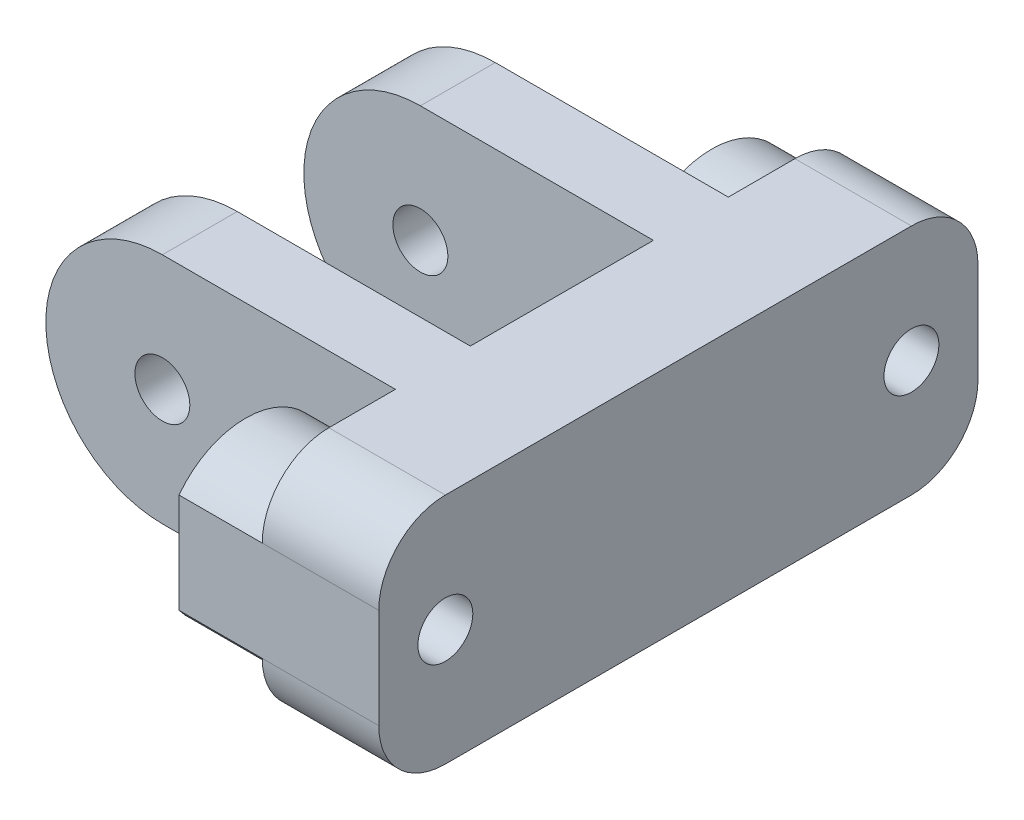
SolidWorks part; units mm, degrees
ref_plane "Front Plane" through (0, 0, 0) normal (0, 0, 1) x (1, 0, 0)
ref_plane "Top Plane" through (0, 0, 0) normal (0, 1, 0) x (1, 0, 0)
ref_plane "Right Plane" through (0, 0, 0) normal (1, 0, 0) x (0, 0, -1)
sketch "Sketch1" plane through (0, 0, 0) normal (0, 0, 1) x (1, 0, 0)
  line L0 (0, 7) -> (14, 7)
  line L1 (14, 7) -> (14, -7)
  line L2 (14, -7) -> (0, -7)
  line L3 (7, 0) -> (14, 0) construction
  circle A0 centre (0, 0) radius 7 construction
  arc A1 (0, 7) -> (0, -7) centre (0, 0) ccw
  circle A2 centre (0, 0) radius 1.65
  dimension "D1" = 14
  dimension "D3" = 3.3
  dimension "D2" = 7
extrude "Boss-Extrude1" add sketch "Sketch1" along normal mid plane 20
sketch "Sketch2" plane through (0, 0, 0) normal (0, 1, 0) x (1, 0, 0)
  line L0 (-7, 10) -> (-7, -10) construction
  line L1 (-7, -5.5) -> (14, -5.5)
  line L2 (-7, -5.5) -> (-7, 5.5)
  line L3 (-7, 5.5) -> (14, 5.5)
  line L4 (14, -5.5) -> (14, 5.5)
  line L5 (14, -10) -> (14, 10) construction
  line L6 (3.5, 10) -> (3.5, 5.5) construction
  line L7 (14, 10) -> (0, 10) construction
  line L8 (3.5, -5.5) -> (3.5, -10) construction
  line L9 (14, -10) -> (0, -10) construction
  dimension "D1" = 11
extrude "Cut-Extrude1" cut sketch "Sketch2" against normal through all both and the other way through all
sketch "Sketch4" plane through (14, 0, 0) normal (1, 0, 0) x (0, 0, -1)
  line L0 (5.5, 7) -> (10, 7) construction
  line L1 (-18, -7) -> (18, -7)
  line L2 (-18, -7) -> (-18, 7)
  line L3 (-18, 7) -> (18, 7)
  line L4 (18, -7) -> (18, 7)
  line L5 (-18, -7) -> (18, 7) construction
  line L6 (-18, 7) -> (18, -7) construction
  line L7 (10, -7) -> (10, 7) construction
  line L8 (10, 7) -> (18, -7) construction
  line L9 (-18, 7) -> (-10, -7) construction
  circle A0 centre (14, 0) radius 1.65
  circle A1 centre (-14, 0) radius 1.65
  point P0 (0, 0)
  dimension "D2" = 3.3
  dimension "D1" = 8
extrude "Boss-Extrude2" add sketch "Sketch4" along normal blind 7
sketch "Sketch5" plane through (14, 0, 0) normal (-1, 0, 0) x (0, 0, 1)
  line L0 (18, 7) -> (18, -7) construction
  line L1 (12.3401, -2.875) -> (15.6599, -2.875)
  line L2 (15.6599, -2.875) -> (17.3198, 0)
  line L3 (17.3198, 0) -> (15.6599, 2.875)
  line L4 (15.6599, 2.875) -> (12.3401, 2.875)
  line L5 (12.3401, 2.875) -> (10.6802, 0)
  line L6 (10.6802, 0) -> (12.3401, -2.875)
  line L7 (10, 7) -> (18, 7) construction
  line L8 (0, 7) -> (0, -7) construction
  line L9 (-5.5, 7) -> (5.5, 7) construction
  line L10 (5.5, -7) -> (-5.5, -7) construction
  line L11 (10, 3) -> (10, -3)
  line L12 (18, 3) -> (18, -3)
  line L13 (10, -7) -> (10, 7) construction
  line L14 (-10.6802, 0) -> (-12.3401, -2.875)
  line L15 (-12.3401, 2.875) -> (-10.6802, 0)
  line L16 (-15.6599, 2.875) -> (-12.3401, 2.875)
  line L17 (-17.3198, 0) -> (-15.6599, 2.875)
  line L18 (-15.6599, -2.875) -> (-17.3198, 0)
  line L19 (-12.3401, -2.875) -> (-15.6599, -2.875)
  line L20 (-18, 3) -> (-18, -3)
  line L21 (-10, 3) -> (-10, -3)
  circle A0 centre (14, 0) radius 2.875 construction
  circle A1 centre (14, 0) radius 4 construction
  arc A2 (10, -3) -> (18, -3) centre (14, 0) ccw
  circle A3 centre (14, 0) radius 5 construction
  arc A4 (18, 3) -> (10, 3) centre (14, 0) ccw
  arc A5 (-18, 3) -> (-10, 3) centre (-14, 0) cw
  arc A6 (-10, -3) -> (-18, -3) centre (-14, 0) cw
  dimension "D1" = 5.75
  dimension "D2" = 1
extrude "Boss-Extrude3" add sketch "Sketch5" along normal blind 5
fillet "Fillet1" radius 4 4 edges at (17.5, 7, 18) (17.5, -7, 18) (17.5, 7, -18) (17.5, -7, -18)
